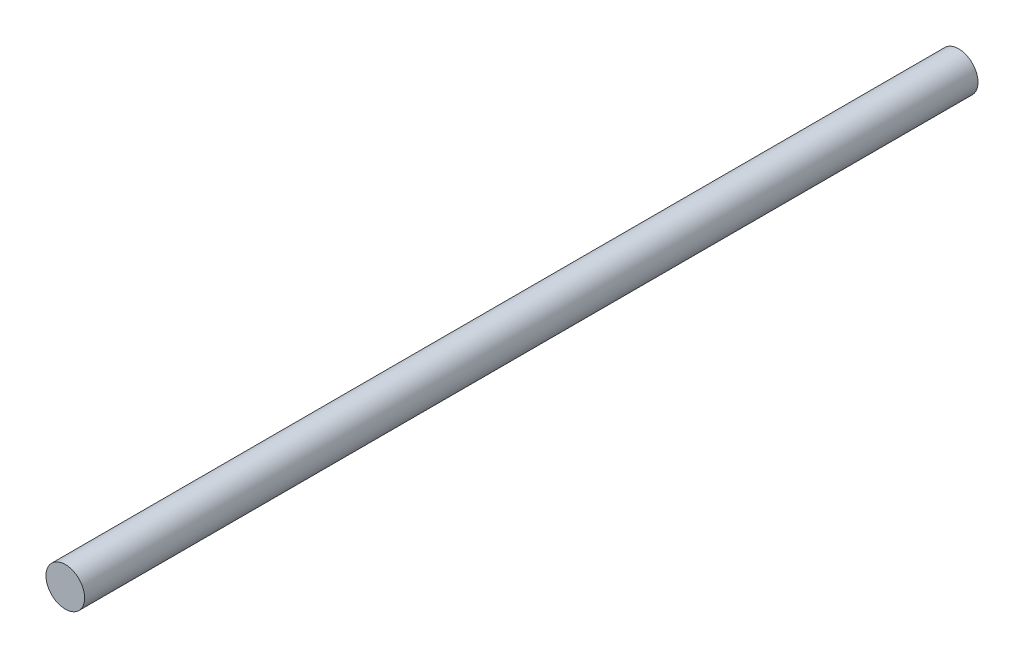
SolidWorks part; units mm, degrees
ref_plane "Alzado" through (0, 0, 0) normal (0, 0, 1) x (1, 0, 0)
ref_plane "Planta" through (0, 0, 0) normal (0, 1, 0) x (1, 0, 0)
ref_plane "Vista lateral" through (0, 0, 0) normal (1, 0, 0) x (0, 0, -1)
sketch "Croquis1" plane through (0, 0, 0) normal (0, 0, 1) x (1, 0, 0)
  circle A0 centre (0, 0) radius 6.5
  dimension "D1" = 13
extrude "Saliente-Extruir1" add sketch "Croquis1" along normal blind 300
